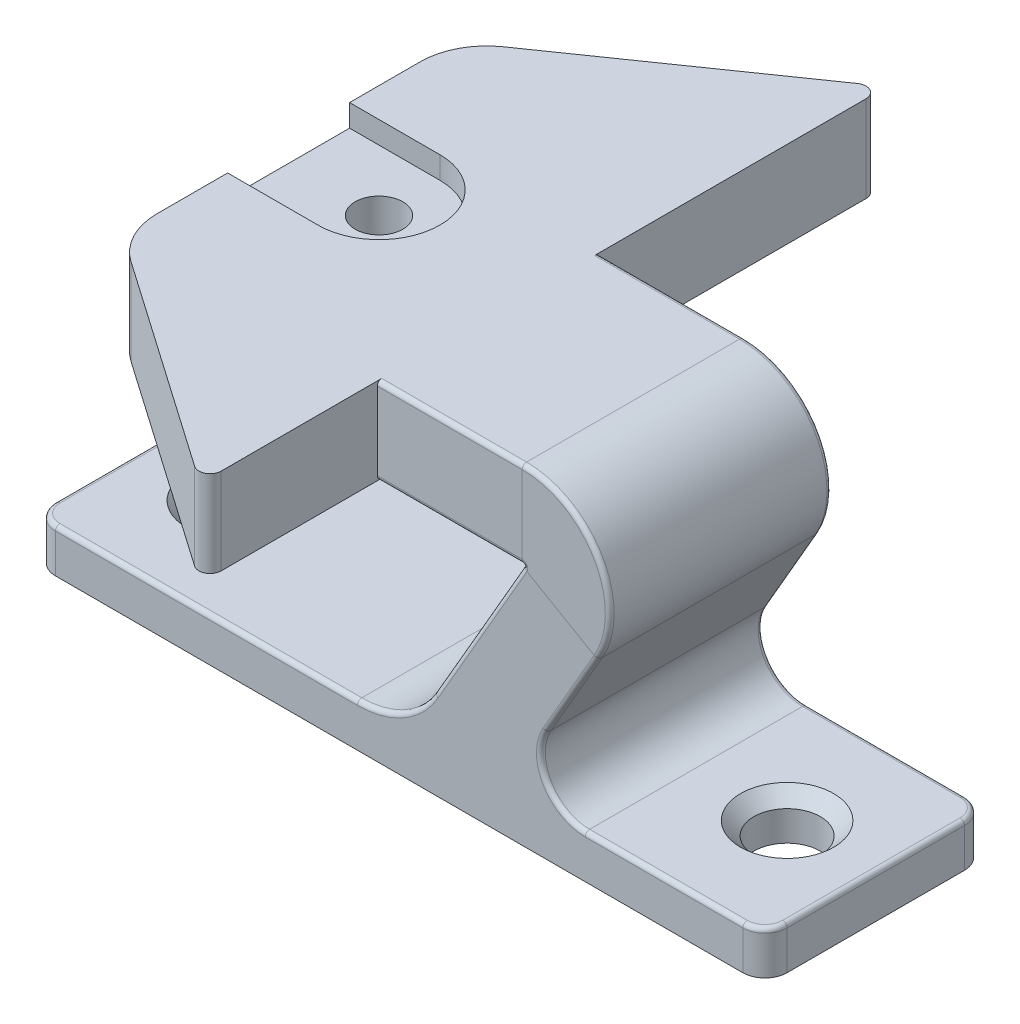
SolidWorks part; units mm, degrees
ref_plane "Front Plane" through (0, 0, 0) normal (0, 0, 1) x (1, 0, 0)
ref_plane "Top Plane" through (0, 0, 0) normal (0, 1, 0) x (1, 0, 0)
ref_plane "Right Plane" through (0, 0, 0) normal (1, 0, 0) x (0, 0, -1)
sketch "Sketch1" plane through (0, 0, 0) normal (0, 1, 0) x (1, 0, 0)
  line L0 (0, 0) -> (-20.6757, 0) construction
  line L1 (-4.075, 0) -> (-4.075, 7.5)
  line L2 (-4.075, 7.5) -> (7.425, 15.5)
  line L3 (7.425, 15.5) -> (7.425, -15.5)
  line L4 (7.425, -15.5) -> (-4.075, -7.5)
  line L5 (-4.075, -7.5) -> (-4.075, 0)
  line L6 (7.425, 0) -> (0, 0) construction
  circle A0 centre (0, 0) radius 1.075
  point P6 (-4.075, -3.75)
  dimension "D1" = 15
  dimension "D3" = 2.15
  dimension "D4" = 3
  dimension "D2" = 31
  dimension "D5" = 11.5
extrude "Boss-Extrude1" add sketch "Sketch1" along normal blind 3.9
sketch "Sketch2" plane through (0, 0, 0) normal (0, -1, 0) x (1, 0, 0)
  line L0 (-4.075, 0) -> (8.4014, 0) construction
  line L1 (-4.075, -7.5) -> (-4.075, 7.5) construction
  line L2 (0.675, 4.75) -> (-5.1161, 4.75)
  line L3 (-5.1161, 4.75) -> (-5.1161, -4.75)
  line L4 (-5.1161, -4.75) -> (0.675, -4.75)
  circle A0 centre (0.675, 0) radius 4.75
  line M4 (-4.075, 7.5) -> (-4.075, -7.5)
  circle M7 centre (0, 0) radius 1.075
  dimension "D1" = 9.5
extrude "Cut-Extrude1" cut sketch "Sketch2" against normal blind 1 contours A0 L2 M4 | A0 L4 M4 | L0 A0 M7 | A0 L0 M7
sketch "Sketch4" plane through (0, 3.9, 0) normal (0, 1, 0) x (1, 0, 0)
  line L0 (0, 2.75) -> (-5.1534, 2.75)
  line L1 (-5.1534, 2.75) -> (-5.1534, -2.75)
  line L2 (-5.1534, -2.75) -> (0, -2.75)
  circle A0 centre (0, 0) radius 2.75
  line M1 (-4.075, 7.5) -> (-4.075, -7.5)
  circle M5 centre (0, 0) radius 1.075
  dimension "D1" = 5.5
extrude "Cut-Extrude2" cut sketch "Sketch4" against normal blind 1 contours A0 L0 L2 M1 | A0 M5
sketch "Sketch6" plane through (7.425, 0, 0) normal (1, 0, 0) x (0, 0, -1)
  line L0 (-15.5, 3.9) -> (15.5, 3.9) construction
  line L1 (-7.5, 3.9) -> (2.5, 3.9)
  line L2 (-7.5, 3.9) -> (-7.5, 0)
  line L3 (-7.5, 0) -> (2.5, 0)
  line L4 (2.5, 3.9) -> (2.5, 0)
  line L5 (-15.5, 0) -> (15.5, 0) construction
  line L6 (-15.5, 3.9) -> (-15.5, 0) construction
  dimension "D1" = 10
  dimension "D2" = 8
extrude "Boss-Extrude2" add sketch "Sketch6" along normal blind 5
sketch "Sketch7" plane through (12.425, 0, 0) normal (1, 0, 0) x (0, 0, -1)
  line L4 (-7.5, 3.9) -> (-7.5, 0)
  line L5 (-7.5, 0) -> (2.5, 0)
  line L6 (2.5, 0) -> (2.5, 3.9)
  line L7 (2.5, 3.9) -> (-7.5, 3.9)
  line L8 (-7.5, 3.9) -> (-7.5, 0)
  line L9 (-7.5, 0) -> (2.5, 0)
  line L10 (2.5, 0) -> (2.5, 3.9)
  line L11 (2.5, 3.9) -> (-7.5, 3.9)
  dimension "D1" = 0
sketch "Sketch8" plane through (0, 0, 0) normal (0, 0, 1) x (1, 0, 0)
  line L0 (12.425, 1.95) -> (13.9609, 1.95)
  line L1 (12.425, 3.9) -> (12.425, 0) construction
  line L2 (15.6929, -1.05) -> (10.5257, -10)
  line L3 (12.425, 0) -> (7.425, 0) construction
  arc A0 (15.6929, -1.05) -> (13.9609, 1.95) centre (13.9609, -0.05) ccw
  point P9 (17.425, 1.95)
  dimension "D4" = 2
  dimension "D1" = 60
  dimension "D2" = 10
  dimension "D3" = 5
sweep "Sweep1" add profiles "Sketch7" path "Sketch8"
sketch "Sketch9" plane through (0, 0, -2.5) normal (0, 0, -1) x (-1, 0, 0)
  line L0 (-12.2144, -10.975) -> (8.0891, -10.975)
  line L1 (8.0891, -10.975) -> (8.0891, -9.025)
  line L2 (8.0891, -9.025) -> (-24.9109, -9.025)
  line L3 (-24.9109, -9.025) -> (-24.9109, -10.975)
  line L4 (-24.9109, -10.975) -> (-12.2144, -10.975)
  arc A2 (-13.9609, 3.9) -> (-17.3817, -2.025) centre (-13.9609, -0.05) ccw construction
  dimension "D1" = 33
  dimension "D2" = 7
extrude "Boss-Extrude3" add sketch "Sketch9" against normal blind 10
sketch "Sketch10" plane through (0, -10.975, 0) normal (0, -1, 0) x (1, 0, 0)
  line L0 (-8.0891, 2.5) -> (24.9109, 2.5) construction
  line L1 (-8.0891, 7.5) -> (-8.0891, -2.5) construction
  line L2 (24.9109, 7.5) -> (24.9109, -2.5) construction
  circle A0 centre (-4.0891, 2.5) radius 1.5
  circle A1 centre (20.9109, 2.5) radius 1.5
  dimension "D1" = 25
  dimension "D2" = 3
  dimension "D3" = 4
extrude "Cut-Extrude3" cut sketch "Sketch10" against normal blind 10
fillet "Fillet2" radius 3 2 edges at (-4.075, 1.95, -7.5) (-4.075, 1.95, 7.5)
fillet "Fillet3" radius 1 4 edges at (24.9109, -10, -2.5) (24.9109, -10, 7.5) (-8.0891, -10, -2.5) (-8.0891, -10, 7.5)
fillet "Fillet4" radius 2 1 edges at (13.3402, -9.025, 2.5)
fillet "Fillet5" radius 4 1 edges at (8.8369, -9.025, 2.5)
chamfer "Chamfer1" distance 0.6 angle 45 2 edges at (20.9109, -9.025, 4) (-4.0891, -9.025, 4)
fillet "Fillet6" radius 0.5 2 edges at (7.425, 1.95, -15.5) (7.425, 1.95, 15.5)
fillet "Fillet7" radius 0.2 26 edges at (10.6929, 0, -2.5) (14.0042, -0.025, -2.5) (10.6929, 0, 7.5) (14.0042, -0.025, 7.5) (11.9979, -3.55, 7.5) (8.5275, -8.4891, 7.5) (-0.2808, -9.025, 7.5) (-7.7962, -9.025, 7.2071) (-8.0891, -9.025, 2.5) (-7.7962, -9.025, -2.2071) (-0.2808, -9.025, -2.5) (8.5275, -8.4891, -2.5) (10.6929, 3.9, -2.5) (10.6929, 3.9, 7.5) (17.3817, 1.925, 7.5) (16.227, -4.025, 7.5) (15.0723, -8.025, 7.5) (20.3576, -9.025, 7.5) (24.618, -9.025, 7.2071) (24.9109, -9.025, 2.5) (24.618, -9.025, -2.2071) (20.3576, -9.025, -2.5) (15.0723, -8.025, -2.5) (16.227, -4.025, -2.5) (11.9979, -3.55, -2.5) (17.3817, 1.925, -2.5)
